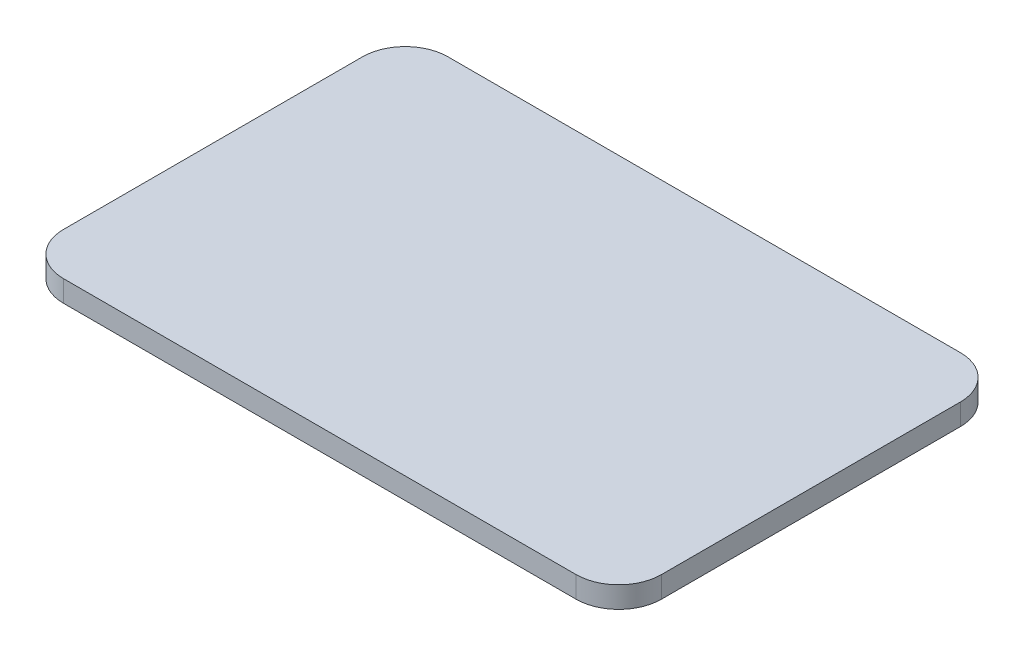
SolidWorks part; units mm, degrees
ref_plane "Front Plane" through (0, 0, 0) normal (0, 0, 1) x (1, 0, 0)
ref_plane "Top Plane" through (0, 0, 0) normal (0, 1, 0) x (1, 0, 0)
ref_plane "Right Plane" through (0, 0, 0) normal (1, 0, 0) x (0, 0, -1)
sketch "Sketch1" plane through (0, 0, 0) normal (0, 1, 0) x (1, 0, 0)
  line L1 (-50.1376, 51.066) -> (89.8624, 51.066)
  line L2 (-50.1376, 51.066) -> (-50.1376, -38.934)
  line L3 (-50.1376, -38.934) -> (89.8624, -38.934)
  line L4 (89.8624, 51.066) -> (89.8624, -38.934)
  dimension "D1" = 90
  dimension "D2" = 140
extrude "Boss-Extrude1" add sketch "Sketch1" along normal blind 5
fillet "Fillet1" radius 10 4 edges at (-50.1376, 2.5, -51.066) (89.8624, 2.5, 38.934) (-50.1376, 2.5, 38.934) (89.8624, 2.5, -51.066)
